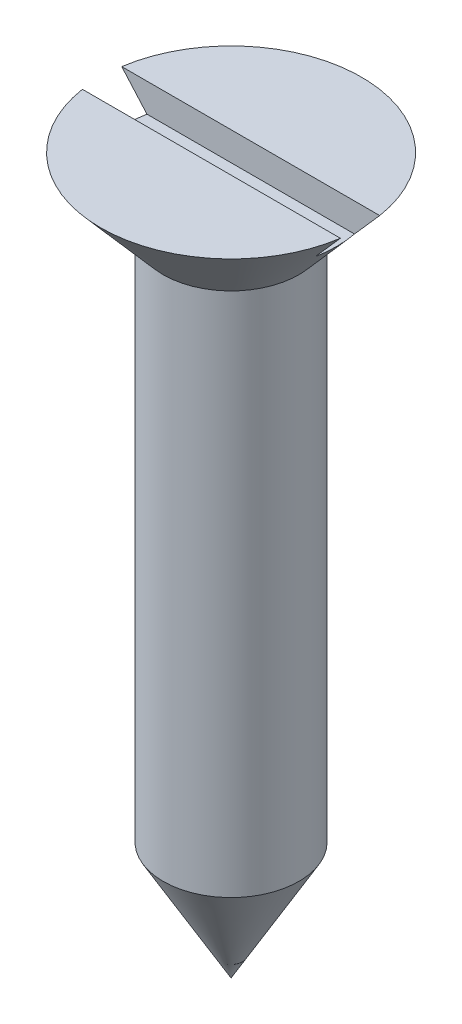
SolidWorks part; units mm, degrees
ref_plane "Front Plane" through (0, 0, 0) normal (0, 0, 1) x (1, 0, 0)
ref_plane "Top Plane" through (0, 0, 0) normal (0, 1, 0) x (1, 0, 0)
ref_plane "Right Plane" through (0, 0, 0) normal (1, 0, 0) x (0, 0, -1)
sketch "Sketch1" plane through (0, 0, 0) normal (0, 1, 0) x (1, 0, 0)
  circle A0 centre (0, 0) radius 2.413
  dimension "D1" = 4.826
extrude "Boss-Extrude1" add sketch "Sketch1" along normal blind 25.4
sketch "Sketch2" plane through (0, 0, 0) normal (0, 0, 1) x (1, 0, 0)
  line L0 (0, 29.4811) -> (0, -1.6248) construction
  line L1 (0, 25.4) -> (4.6355, 25.4)
  line L2 (4.6355, 25.4) -> (0, 20.0675)
  line L3 (0, 20.0675) -> (0, 25.4)
  line L4 (2.413, 25.4) -> (-2.413, 25.4) construction
  dimension "D1" = 41
  dimension "D2" = 9.271
revolve "Revolve1" add sketch "Sketch2" angle 360 about L0
sketch "Sketch3" plane through (0, 0, 0) normal (0, 0, 1) x (1, 0, 0)
  line L0 (0, 26.3344) -> (0, -2.501) construction
  line L1 (0, 0) -> (2.413, 4.1794)
  line L2 (2.413, 0) -> (2.413, 22.8433) construction
  line L3 (2.413, 4.1794) -> (2.413, -0.635)
  line L4 (0, 0) -> (0, -0.635)
  line L5 (0, -0.635) -> (2.413, -0.635)
  dimension "D1" = 0.635
  dimension "D2" = 30
revolve "Cut-Revolve2" cut sketch "Sketch3" angle 360 about L0
sketch "Sketch4" plane through (0, 25.4, 0) normal (0, 1, 0) x (1, 0, 0)
  line L0 (-4.6355, 5.5385) -> (-4.6355, -5.4327) construction
  line L1 (4.6355, 5.1155) -> (4.6355, -6.9132) construction
  line L3 (-5.9055, 0.6985) -> (5.9055, 0.6985)
  line L4 (-5.9055, 0.6985) -> (-5.9055, -0.6985)
  line L5 (-5.9055, -0.6985) -> (5.9055, -0.6985)
  line L6 (5.9055, 0.6985) -> (5.9055, -0.6985)
  line L7 (-5.9055, 0.6985) -> (5.9055, -0.6985) construction
  line L8 (-5.9055, -0.6985) -> (5.9055, 0.6985) construction
  circle A0 centre (0, 0) radius 4.6355 construction
  point P6 (0, 0)
  point P12 (-4.6355, 0.6985)
  point P13 (4.6355, 0.6985)
  point P14 (4.6355, -0.6985)
  point P15 (-4.6355, -0.6985)
  dimension "D1" = 1.27
  dimension "D2" = 1.397
extrude "Cut-Extrude1" cut sketch "Sketch4" against normal blind 1.016
